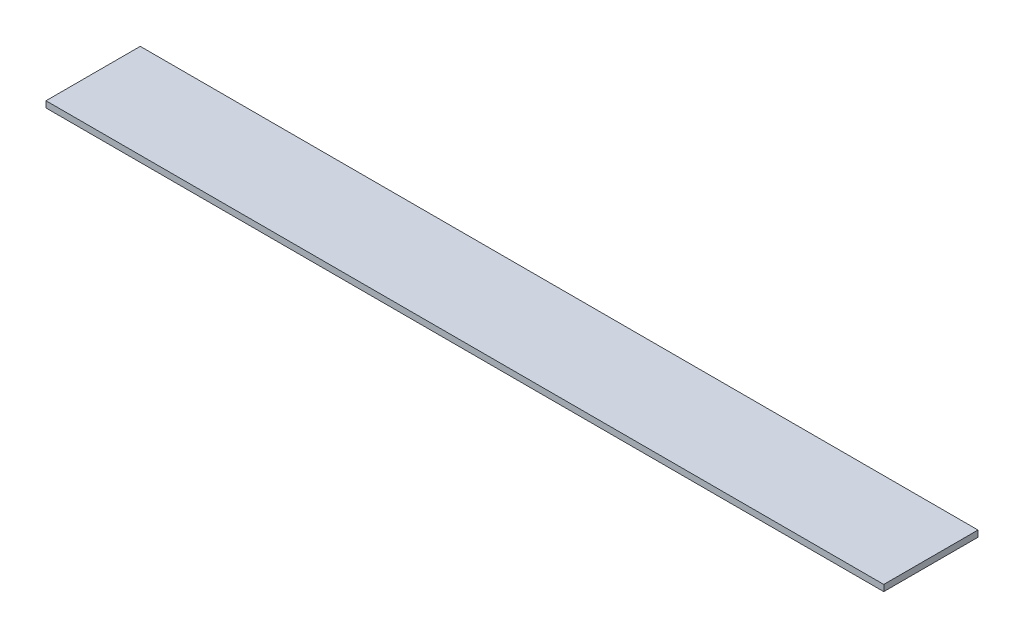
SolidWorks part; units mm, degrees
ref_plane "Front Plane" through (0, 0, 0) normal (0, 0, 1) x (1, 0, 0)
ref_plane "Top Plane" through (0, 0, 0) normal (0, 1, 0) x (1, 0, 0)
ref_plane "Right Plane" through (0, 0, 0) normal (1, 0, 0) x (0, 0, -1)
sketch "Sketch1" plane through (0, 0, 0) normal (0, 1, 0) x (1, 0, 0)
  line L1 (-70.361, 49.9001) -> (329.639, 49.9001)
  line L2 (-70.361, 49.9001) -> (-70.361, 4.9001)
  line L3 (-70.361, 4.9001) -> (329.639, 4.9001)
  line L4 (329.639, 49.9001) -> (329.639, 4.9001)
  dimension "D1" = 45
  dimension "D2" = 400
extrude "Boss-Extrude1" add sketch "Sketch1" along normal blind 3
